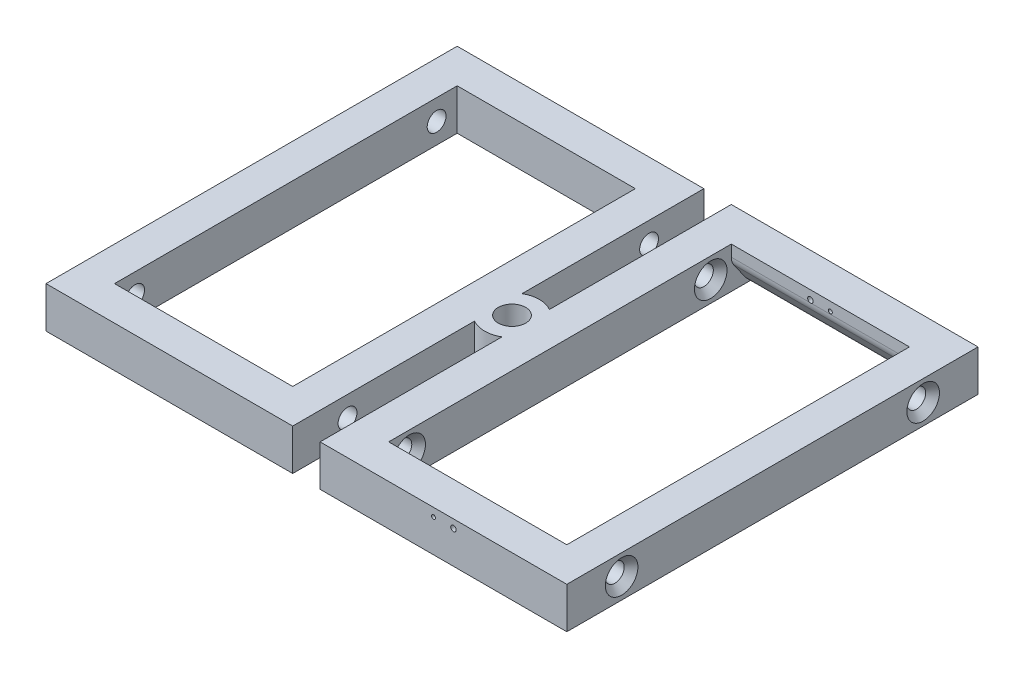
SolidWorks part; units mm, degrees
ref_plane "Front Plane" through (0, 0, 0) normal (0, 0, 1) x (1, 0, 0)
ref_plane "Top Plane" through (0, 0, 0) normal (0, 1, 0) x (1, 0, 0)
ref_plane "Right Plane" through (0, 0, 0) normal (1, 0, 0) x (0, 0, -1)
sketch "Sketch3" plane through (0, 0, 0) normal (0, 1, 0) x (1, 0, 0)
  line L0 (17.78, 63.5) -> (17.78, -63.5)
  line L7 (17.78, 63.5) -> (83.82, 63.5)
  line L8 (83.82, 63.5) -> (83.82, -63.5)
  line L9 (83.82, -63.5) -> (17.78, -63.5)
  line L10 (96.52, -76.2) -> (5.08, -76.2)
  line L11 (5.08, 76.2) -> (5.08, -76.2)
  line L12 (5.08, 76.2) -> (96.52, 76.2)
  line L13 (96.52, 76.2) -> (96.52, -76.2)
  circle A0 centre (0, 0) radius 5.08
  circle A1 centre (0, 0) radius 10.16
  point P5 (17.78, 0)
  dimension "D1" = 10.16
  dimension "D3" = 66.04
  dimension "D4" = 127
  dimension "D2" = 5.08
  dimension "D5" = 12.7
extrude "Boss-Extrude1" add sketch "Sketch3" along normal blind 15.24 contours A1 L11 L10 L13 L12 L8 L9 L0 L7 | L11 A1 A0 | L11 A1
sketch "Sketch4" plane through (5.08, 0, 0) normal (-1, 0, 0) x (0, 0, 1)
  line L0 (-76.2, 15.24) -> (-76.2, 0) construction
  line L1 (76.2, 15.24) -> (76.2, 0) construction
  circle A0 centre (-55.88, 7.62) radius 3.4925
  circle A1 centre (55.88, 7.62) radius 3.4925
  point P4 (0, 0)
  point P5 (0, 0)
  point P8 (-76.2, 7.62)
  dimension "D1" = 6.985
  dimension "D2" = 6.985
  dimension "D3" = 20.32
  dimension "D4" = 20.32
extrude "Cut-Extrude1" cut sketch "Sketch4" against normal up to surface (91.44 mm away) up to face at (96.52, 7.62, 0)
chamfer "Chamfer1" distance 6.604 angle 55 2 edges at (50.8, 0, 63.5) (50.8, 0, -63.5)
chamfer "Chamfer2" distance 2.54 angle 45 4 edges at (17.78, 7.62, 52.3875) (17.78, 7.62, -59.3725) (96.52, 7.62, -59.3725) (96.52, 7.62, 52.3875)
fillet "Fillet1" radius 5.08 4 edges at (50.8, 0, 70.104) (50.8, 9.4315, 63.5) (50.8, 0, -70.104) (50.8, 9.4315, -63.5)
sketch "Sketch5" plane through (0, 0, -63.5) normal (0, 0, 1) x (1, 0, 0)
  circle A0 centre (47.1067, 11.9687) radius 1.016
  ellipse E1 centre (47.1067, 11.9687) end of major axis (46.0907, 11.9687) minor radius 1.016 (46.355, 11.2853) -> (46.355, 12.6522) ccw
  ellipse E3 centre (54.4727, 11.9687) end of major axis (53.7361, 11.9687) minor radius 0.7366
  line M3 (17.78, 11.0332) -> (83.82, 11.0332)
extrude "Cut-Extrude2" cut sketch "Sketch5" against normal blind 12.7 contours A0 M3 | E3 | A0 M3
sketch "Sketch6" plane through (0, 0, 63.5) normal (0, 0, -1) x (-1, 0, 0)
  circle A0 centre (-54.4933, 12.1473) radius 1.016
  ellipse E1 centre (-54.4933, 12.1473) end of major axis (-53.4773, 12.1473) minor radius 1.016 (-55.245, 11.4638) -> (-55.245, 12.8307) ccw
  ellipse E3 centre (-47.1273, 12.1473) end of major axis (-46.3907, 12.1473) minor radius 0.7366
extrude "Cut-Extrude3" cut sketch "Sketch6" against normal blind 12.7 contours A0 | E3
mirror "Mirror1" about plane through (0, 0, 0) normal (1, 0, 0) of "Cut-Extrude1", "Boss-Extrude1"
